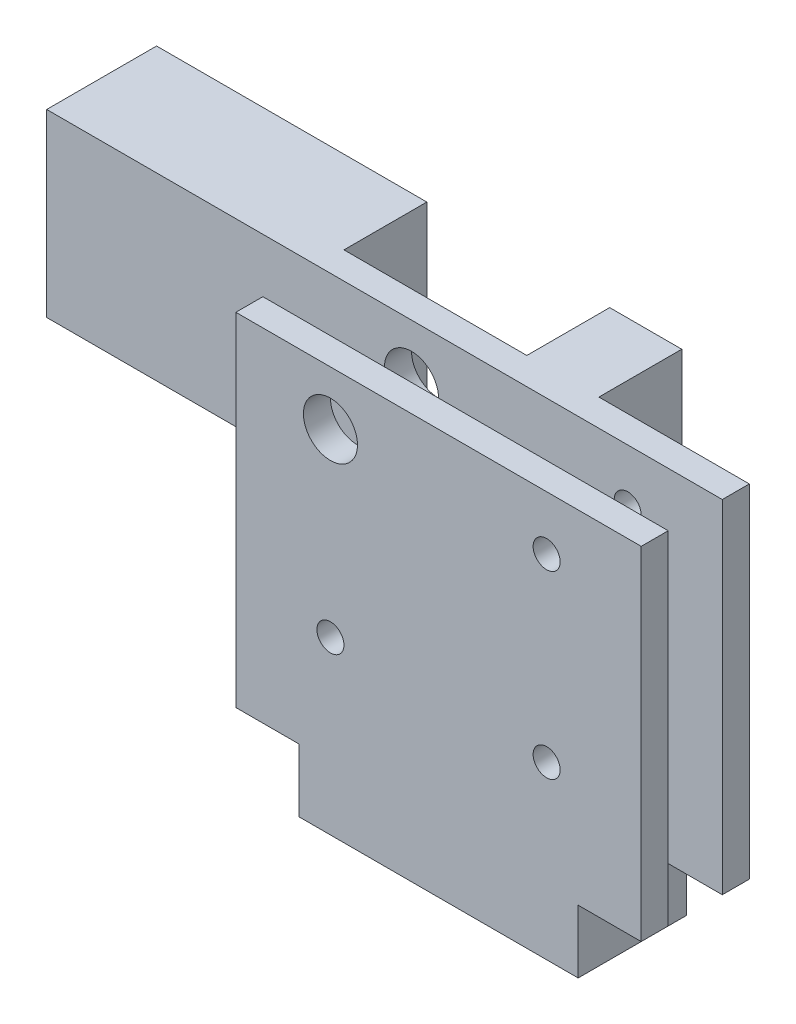
SolidWorks part; units mm, degrees
ref_plane "前视基准面" through (0, 0, 0) normal (0, 0, 1) x (1, 0, 0)
ref_plane "上视基准面" through (0, 0, 0) normal (0, 1, 0) x (1, 0, 0)
ref_plane "右视基准面" through (0, 0, 0) normal (1, 0, 0) x (0, 0, -1)
other "Configuration Table"
sketch "草图1" plane through (0, 0, 0) normal (0, 0, 1) x (1, 0, 0)
  line L1 (22.5, -22.5) -> (-22.5, -22.5)
  line L2 (22.5, -22.5) -> (22.5, 22.5)
  line L3 (22.5, 22.5) -> (-22.5, 22.5)
  line L4 (-22.5, -22.5) -> (-22.5, 22.5)
  line L5 (22.5, -22.5) -> (-22.5, 22.5) construction
  line L6 (22.5, 22.5) -> (-22.5, -22.5) construction
  point P0 (0, 0)
  dimension "D1" = 45
  dimension "D2" = 45
extrude "凸台-拉伸1" add sketch "草图1" along normal blind 12
sketch "草图2" plane through (-22.5, 0, 0) normal (-1, 0, 0) x (0, 0, 1)
  line L0 (6, 22.5) -> (6, -22.5) construction
  line L1 (12, 22.5) -> (0, 22.5) construction
  line L2 (12, -22.5) -> (0, -22.5) construction
  line L4 (9, -15.5) -> (3, -15.5)
  line L5 (9, -15.5) -> (9, 22.5)
  line L6 (9, 22.5) -> (3, 22.5)
  line L7 (3, -15.5) -> (3, 22.5)
  line L8 (9, -15.5) -> (3, 22.5) construction
  line L9 (9, 22.5) -> (3, -15.5) construction
  point P6 (6, 3.5)
  dimension "D1" = 38
  dimension "D2" = 6
extrude "切除-拉伸1" cut sketch "草图2" against normal through all
sketch "草图3" plane through (0, 0, 12) normal (0, 0, 1) x (1, 0, 0)
  line L0 (0, 22.5) -> (0, -22.5) construction
  line L1 (22.5, 22.5) -> (-22.5, 22.5) construction
  line L2 (-22.5, -22.5) -> (22.5, -22.5) construction
  line L3 (0, 16.5) -> (12, 16.5) construction
  line L4 (0, 16.5) -> (-12, 16.5) construction
  circle A0 centre (-12, 16.5) radius 3
  circle A1 centre (12, 16.5) radius 1.5
  dimension "D3" = 6
  dimension "D4" = 3
  dimension "D1" = 12
  dimension "D2" = 6
extrude "切除-拉伸2" cut sketch "草图3" against normal through all
sketch "草图4" plane through (0, 0, 12) normal (0, 0, 1) x (1, 0, 0)
  line L0 (-12, 16.5) -> (-12, -3.5) construction
  line L1 (12, 16.5) -> (12, -3.5) construction
  circle A0 centre (-12, -3.5) radius 1.5
  circle A1 centre (12, -3.5) radius 1.5
  dimension "D2" = 3
  dimension "D1" = 20
extrude "切除-拉伸3" cut sketch "草图4" against normal through all
sketch "草图6" plane through (0, -22.5, 0) normal (0, -1, 0) x (1, 0, 0)
  line L0 (-22.5, 0) -> (22.5, 0) construction
  line L1 (-22.5, 12) -> (-15.5, 12)
  line L2 (-22.5, 12) -> (-22.5, 0)
  line L3 (-22.5, 0) -> (-15.5, 0)
  line L4 (-15.5, 12) -> (-15.5, 0)
  line L5 (-22.5, 12) -> (22.5, 12) construction
  line L6 (22.5, 0) -> (15.5, 0)
  line L7 (22.5, 0) -> (22.5, 12)
  line L8 (22.5, 12) -> (15.5, 12)
  line L9 (15.5, 0) -> (15.5, 12)
  dimension "D1" = 7
  dimension "D2" = 7
extrude "切除-拉伸4" cut sketch "草图6" against normal blind 7
sketch "草图7" plane through (0, 0, 0) normal (0, 0, -1) x (-1, 0, 0)
  line L0 (12, 16.5) -> (-2.8, 16.5) construction
  line L1 (12, 16.5) -> (46.8, 16.5) construction
  line L2 (-22.5, 22.5) -> (22.5, 22.5) construction
  line L3 (22.5, 22.5) -> (52.5, 22.5)
  line L4 (22.5, 22.5) -> (22.5, 2.5)
  line L5 (22.5, 2.5) -> (52.5, 2.5)
  line L6 (52.5, 22.5) -> (52.5, 2.5)
  line L8 (-5.8, 22.5) -> (2.2, 22.5)
  line L9 (-5.8, 22.5) -> (-5.8, 2.5)
  line L10 (-5.8, 2.5) -> (2.2, 2.5)
  line L11 (2.2, 22.5) -> (2.2, 2.5)
  dimension "D1" = 14.8
  dimension "D2" = 34.8
  dimension "D3" = 20
  dimension "D4" = 30
  dimension "D5" = 20
  dimension "D6" = 8
  dimension "D7" = 3
extrude "凸台-拉伸2" add sketch "草图7" along normal blind 9.2
sketch "草图9" plane through (0, 0, 0) normal (0, 0, 1) x (1, 0, 0)
  line L4 (-22.5, 2.5) -> (-22.5, 22.5)
  line L5 (-22.5, 22.5) -> (-52.5, 22.5)
  line L6 (-52.5, 22.5) -> (-52.5, 2.5)
  line L7 (-52.5, 2.5) -> (-22.5, 2.5)
  line L8 (-22.5, 2.5) -> (-22.5, 22.5)
  line L9 (-22.5, 22.5) -> (-52.5, 22.5)
  line L10 (-52.5, 22.5) -> (-52.5, 2.5)
  line L11 (-52.5, 2.5) -> (-22.5, 2.5)
  dimension "D1" = 0
extrude "凸台-拉伸4" add sketch "草图9" along normal blind 3
